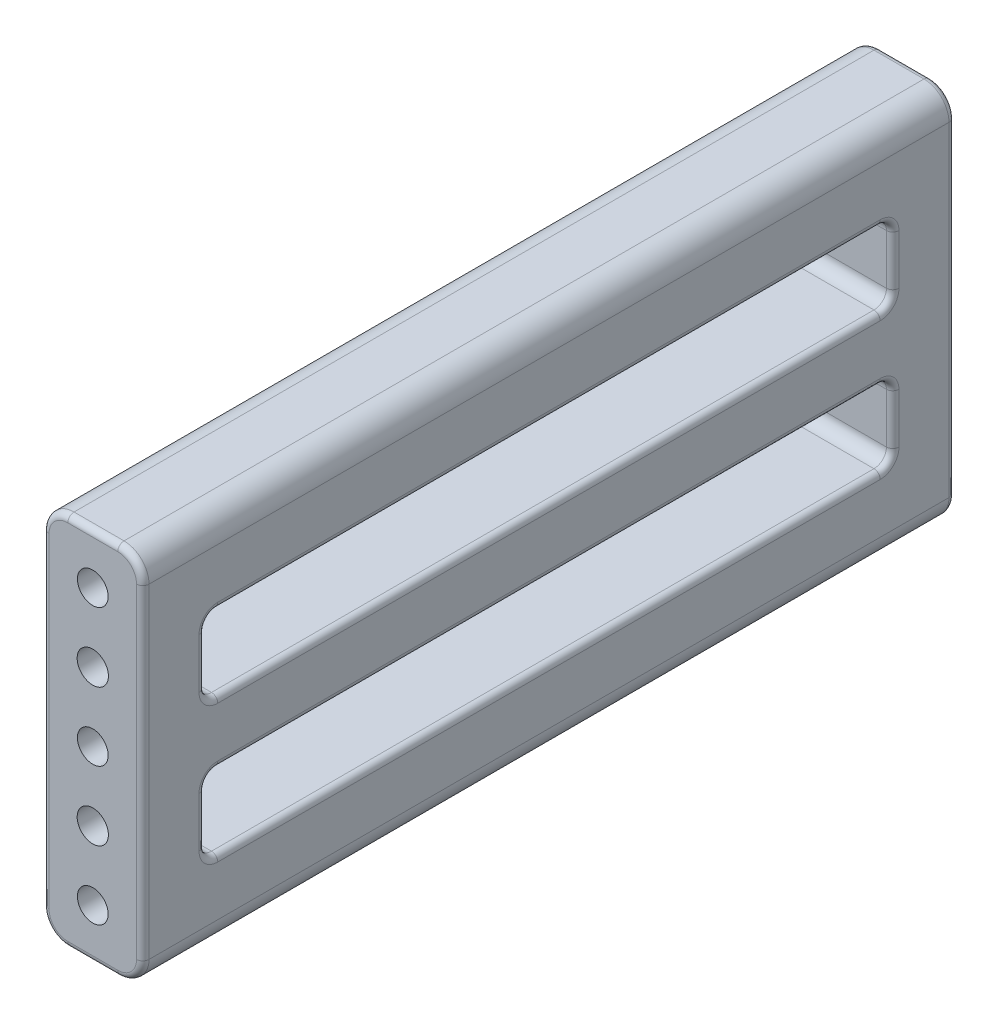
SolidWorks part; units mm, degrees
material "6061 Alloy"
ref_plane "Front Plane" through (0, 0, 0) normal (0, 0, 1) x (1, 0, 0)
ref_plane "Top Plane" through (0, 0, 0) normal (0, 1, 0) x (1, 0, 0)
ref_plane "Right Plane" through (0, 0, 0) normal (1, 0, 0) x (0, 0, -1)
sketch "Sketch1" plane through (0, 0, 0) normal (1, 0, 0) x (0, 0, -1)
  line L1 (-32.5, 15) -> (32.5, 15)
  line L2 (-32.5, 15) -> (-32.5, -15)
  line L3 (-32.5, -15) -> (32.5, -15)
  line L4 (32.5, 15) -> (32.5, -15)
  line L5 (-32.5, 15) -> (32.5, -15) construction
  line L6 (-32.5, -15) -> (32.5, 15) construction
  point P0 (0, 0)
  dimension "D1" = 65
  dimension "D2" = 30
extrude "Boss-Extrude1" add sketch "Sketch1" along normal blind 8
fillet "Fillet1" radius 2 4 edges at (8, -15, 0) (0, -15, 0) (0, 15, 0) (8, 15, 0)
fillet "Fillet2" radius 0.5 16 edges at (7.4142, 14.4142, -32.5) (4, 15, -32.5) (0.5858, 14.4142, -32.5) (0, 0, -32.5) (0.5858, -14.4142, -32.5) (4, -15, -32.5) (7.4142, -14.4142, -32.5) (8, 0, -32.5) (0.5858, -14.4142, 32.5) (0, 0, 32.5) (0.5858, 14.4142, 32.5) (4, 15, 32.5) (7.4142, 14.4142, 32.5) (8, 0, 32.5) (7.4142, -14.4142, 32.5) (4, -15, 32.5)
sketch "Sketch2" plane through (0, 0, -32.5) normal (0, 0, -1) x (-1, 0, 0)
  circle A0 centre (-4, 0) radius 1.2295
  circle A1 centre (-4, 11) radius 1.2295
  circle A2 centre (-4, -11) radius 1.2295
  dimension "D2" = 2.459
  dimension "D3" = 11
  dimension "D4" = 11
  dimension "D1" = 4
extrude "Cut-Extrude1" cut sketch "Sketch2" against normal blind 10
sketch "Sketch3" plane through (8, 0, 0) normal (1, 0, 0) x (0, 0, -1)
  line L0 (-32.5, 0) -> (32.5, 0) construction
  line L1 (-27.5, 8.5) -> (27.5, 8.5)
  line L2 (-27.5, 8.5) -> (-27.5, 2.5)
  line L3 (-27.5, 2.5) -> (27.5, 2.5)
  line L4 (27.5, 8.5) -> (27.5, 2.5)
  line L9 (-32.5, -13) -> (-32.5, 13) construction
  line L10 (32.5, 13) -> (32.5, -13) construction
  line L12 (-27.5, -2.5) -> (27.5, -2.5)
  line L13 (27.5, -8.5) -> (27.5, -2.5)
  line L14 (-27.5, -8.5) -> (27.5, -8.5)
  line L15 (-27.5, -8.5) -> (-27.5, -2.5)
  line L16 (0, 15) -> (0, -15) construction
  line L17 (-32, 15) -> (32, 15) construction
  line L18 (32, -15) -> (-32, -15) construction
  dimension "D1" = 55
  dimension "D3" = 8.5
  dimension "D4" = 2.5
extrude "Cut-Extrude2" cut sketch "Sketch3" against normal blind 10
fillet "Fillet3" radius 1 8 edges at (4, -8.5, -27.5) (4, -2.5, -27.5) (4, -8.5, 27.5) (4, -2.5, 27.5) (4, 2.5, -27.5) (4, 8.5, -27.5) (4, 2.5, 27.5) (4, 8.5, 27.5)
fillet "Fillet4" radius 0.5 32 edges at (0, -8.2071, -27.2071) (0, -8.5, 0) (0, -8.2071, 27.2071) (0, -5.5, 27.5) (0, -2.7929, 27.2071) (0, -2.5, 0) (0, -2.7929, -27.2071) (0, -5.5, -27.5) (0, 2.7929, -27.2071) (0, 2.5, 0) (0, 2.7929, 27.2071) (0, 5.5, 27.5) (0, 8.2071, 27.2071) (0, 8.5, 0) (0, 8.2071, -27.2071) (0, 5.5, -27.5) (8, -8.2071, 27.2071) (8, -8.5, 0) (8, -8.2071, -27.2071) (8, -5.5, -27.5) (8, -2.7929, -27.2071) (8, -2.5, 0) (8, -2.7929, 27.2071) (8, -5.5, 27.5) (8, 2.7929, 27.2071) (8, 2.5, 0) (8, 2.7929, -27.2071) (8, 5.5, -27.5) (8, 8.2071, -27.2071) (8, 8.5, 0) (8, 8.2071, 27.2071) (8, 5.5, 27.5)
hole_wizard "Ø2.5mm Dowel Hole1" positions "Sketch5" profile "Sketch6" hole size "Ø2.5" standard "ANSI Metric"
sketch "Sketch5" plane through (0, 0, -32.5) normal (0, 0, -1) x (-1, 0, 0)
  line L0 (0, 13) -> (0, -13) construction
  circle A0 centre (-4, 0) radius 1.2295 construction
  circle A1 centre (-4, 0) radius 1.2295 construction
  point P0 (-4, 5.5)
  point P2 (-4, -5.5)
  dimension "D2" = 4
  dimension "D1" = 5.5
  dimension "D3" = 5.5
sketch "Sketch6" plane through (4, 5.5, -32.5) normal (1, 0, 0) x (0, 1, 0)
  line L0 (0, 0) -> (0, 4.7511)
  line L1 (0, 4.7511) -> (1.25, 4)
  line L2 (1.25, 4) -> (1.25, 0)
  line L5 (1.25, 0) -> (0, 0)
  line L10 (0, 4.7511) -> (-1.25, 4) construction
  line L11 (0, -6.35) -> (0, 107.95) construction
  dimension "Hole Dia." = 2.5
  dimension "Hole Depth" = 4
  dimension "Drill Angle" = 118
mirror "Mirror1" about plane through (0, 0, 0) normal (0, 0, 1) of "Ø2.5mm Dowel Hole1", "Cut-Extrude1"
